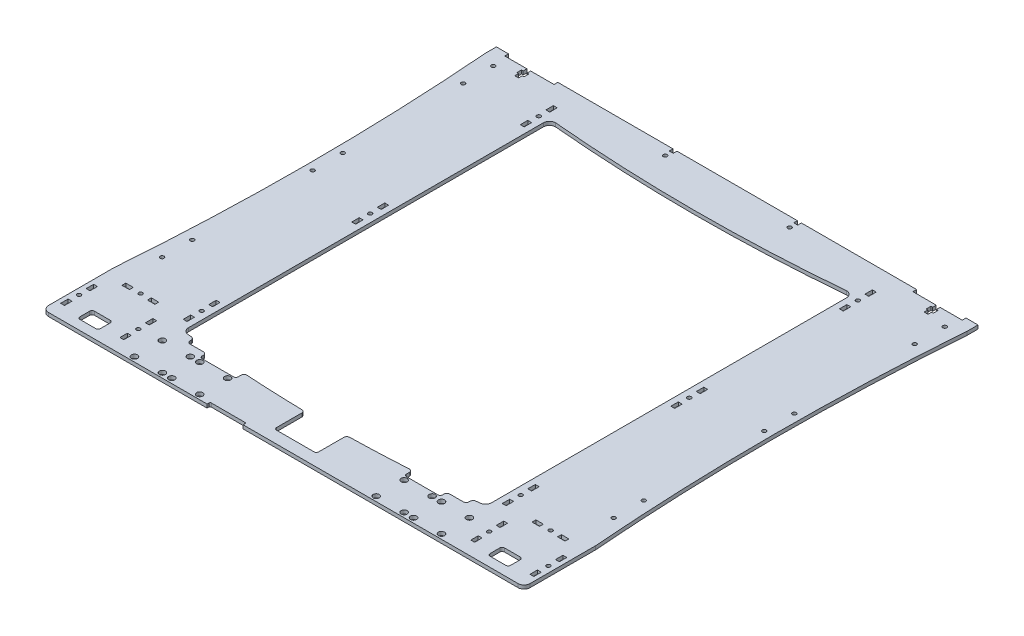
SolidWorks part; units mm, degrees
ref_plane "Alzado" through (0, 0, 0) normal (0, 0, 1) x (1, 0, 0)
ref_plane "Planta" through (0, 0, 0) normal (0, 1, 0) x (1, 0, 0)
ref_plane "Vista lateral" through (0, 0, 0) normal (1, 0, 0) x (0, 0, -1)
sketch "Croquis1" plane through (0, 0, 0) normal (0, 1, 0) x (1, 0, 0)
  line L0 (200, 377) -> (200, 0) construction
  line L1 (0, 0) -> (400, 0)
  line L2 (0, 0) -> (0, 377)
  line L3 (0, 377) -> (10, 377)
  line L4 (400, 0) -> (400, 377)
  line L5 (52.7, 17.8) -> (55.9, 17.8)
  line L6 (3.5, 17.8) -> (6.7, 17.8)
  line L7 (3.5, 17.8) -> (3.5, 11.6)
  line L8 (3.5, 11.6) -> (6.7, 11.6)
  line L9 (6.7, 17.8) -> (6.7, 11.6)
  line L10 (3.5, 39) -> (6.7, 39)
  line L11 (3.5, 39) -> (3.5, 32.8)
  line L12 (3.5, 32.8) -> (6.7, 32.8)
  line L13 (6.7, 39) -> (6.7, 32.8)
  line L14 (52.7, 17.8) -> (52.7, 11.6)
  line L15 (52.7, 11.6) -> (55.9, 11.6)
  line L16 (55.9, 17.8) -> (55.9, 11.6)
  line L17 (52.7, 39) -> (55.9, 39)
  line L18 (52.7, 39) -> (52.7, 32.8)
  line L19 (52.7, 32.8) -> (55.9, 32.8)
  line L20 (55.9, 39) -> (55.9, 32.8)
  line L21 (69.1, 218.4) -> (69.1, 212.2)
  line L22 (16, 53.2) -> (22.2, 53.2)
  line L23 (16, 53.2) -> (16, 50)
  line L24 (16, 50) -> (22.2, 50)
  line L25 (22.2, 53.2) -> (22.2, 50)
  line L26 (37.2, 53.2) -> (43.4, 53.2)
  line L27 (37.2, 53.2) -> (37.2, 50)
  line L28 (37.2, 50) -> (43.4, 50)
  line L29 (43.4, 53.2) -> (43.4, 50)
  line L30 (65.9, 57.2) -> (69.1, 57.2)
  line L31 (65.9, 57.2) -> (65.9, 51)
  line L32 (65.9, 51) -> (69.1, 51)
  line L33 (69.1, 57.2) -> (69.1, 51)
  line L34 (65.9, 78.4) -> (69.1, 78.4)
  line L35 (65.9, 78.4) -> (65.9, 72.2)
  line L36 (65.9, 72.2) -> (69.1, 72.2)
  line L37 (69.1, 78.4) -> (69.1, 72.2)
  line L38 (65.9, 218.4) -> (69.1, 218.4)
  line L39 (65.9, 218.4) -> (65.9, 212.2)
  line L40 (65.9, 212.2) -> (69.1, 212.2)
  line L41 (65.9, 197.2) -> (69.1, 197.2)
  line L42 (69.1, 197.2) -> (69.1, 191)
  line L43 (65.9, 197.2) -> (65.9, 191)
  line L44 (65.9, 191) -> (69.1, 191)
  line L45 (69.1, 78.4) -> (69.1, 218.4) construction
  line L46 (69.1, 337.2) -> (69.1, 331)
  line L47 (65.9, 337.2) -> (69.1, 337.2)
  line L48 (65.9, 337.2) -> (65.9, 331)
  line L49 (65.9, 331) -> (69.1, 331)
  line L50 (65.9, 352.2) -> (69.1, 352.2)
  line L51 (69.1, 358.4) -> (69.1, 352.2)
  line L52 (65.9, 358.4) -> (69.1, 358.4)
  line L53 (65.9, 358.4) -> (65.9, 352.2)
  line L54 (69.1, 197.2) -> (69.1, 337.2) construction
  line L55 (330.9, 197.2) -> (330.9, 337.2) construction
  line L56 (330.9, 78.4) -> (330.9, 218.4) construction
  line L57 (334.1, 358.4) -> (334.1, 352.2)
  line L58 (334.1, 358.4) -> (330.9, 358.4)
  line L59 (330.9, 358.4) -> (330.9, 352.2)
  line L60 (334.1, 352.2) -> (330.9, 352.2)
  line L61 (334.1, 331) -> (330.9, 331)
  line L62 (334.1, 337.2) -> (334.1, 331)
  line L63 (334.1, 337.2) -> (330.9, 337.2)
  line L64 (330.9, 337.2) -> (330.9, 331)
  line L65 (334.1, 191) -> (330.9, 191)
  line L66 (334.1, 197.2) -> (334.1, 191)
  line L67 (330.9, 197.2) -> (330.9, 191)
  line L68 (334.1, 197.2) -> (330.9, 197.2)
  line L69 (334.1, 212.2) -> (330.9, 212.2)
  line L70 (334.1, 218.4) -> (334.1, 212.2)
  line L71 (334.1, 218.4) -> (330.9, 218.4)
  line L72 (330.9, 78.4) -> (330.9, 72.2)
  line L73 (334.1, 72.2) -> (330.9, 72.2)
  line L74 (334.1, 78.4) -> (334.1, 72.2)
  line L75 (334.1, 78.4) -> (330.9, 78.4)
  line L76 (330.9, 57.2) -> (330.9, 51)
  line L77 (334.1, 51) -> (330.9, 51)
  line L78 (334.1, 57.2) -> (334.1, 51)
  line L79 (334.1, 57.2) -> (330.9, 57.2)
  line L80 (356.6, 53.2) -> (356.6, 50)
  line L81 (362.8, 50) -> (356.6, 50)
  line L82 (362.8, 53.2) -> (362.8, 50)
  line L83 (362.8, 53.2) -> (356.6, 53.2)
  line L84 (377.8, 53.2) -> (377.8, 50)
  line L85 (384, 50) -> (377.8, 50)
  line L86 (384, 53.2) -> (384, 50)
  line L87 (384, 53.2) -> (377.8, 53.2)
  line L88 (330.9, 218.4) -> (330.9, 212.2)
  line L89 (344.1, 39) -> (344.1, 32.8)
  line L90 (347.3, 32.8) -> (344.1, 32.8)
  line L91 (347.3, 39) -> (347.3, 32.8)
  line L92 (347.3, 39) -> (344.1, 39)
  line L93 (344.1, 17.8) -> (344.1, 11.6)
  line L94 (347.3, 11.6) -> (344.1, 11.6)
  line L95 (347.3, 17.8) -> (347.3, 11.6)
  line L96 (393.3, 39) -> (393.3, 32.8)
  line L97 (396.5, 32.8) -> (393.3, 32.8)
  line L98 (396.5, 39) -> (396.5, 32.8)
  line L99 (396.5, 39) -> (393.3, 39)
  line L100 (393.3, 17.8) -> (393.3, 11.6)
  line L101 (396.5, 11.6) -> (393.3, 11.6)
  line L102 (396.5, 17.8) -> (396.5, 11.6)
  line L103 (396.5, 17.8) -> (393.3, 17.8)
  line L104 (347.3, 17.8) -> (344.1, 17.8)
  line L105 (400, 0) -> (400, 377)
  line L106 (51, 377) -> (146.7, 377)
  line L108 (10, 377) -> (10, 373.9)
  line L109 (10, 373.9) -> (28.4, 373.9)
  line L110 (51, 377) -> (51, 373.9)
  line L111 (31.6, 373.9) -> (51, 373.9)
  line L113 (28.4, 373.9) -> (28.4, 370.9)
  line L114 (28.4, 363.9) -> (31.6, 363.9)
  line L115 (31.6, 373.9) -> (31.6, 370.9)
  line L116 (27, 370.9) -> (28.4, 370.9)
  line L117 (27, 370.9) -> (27, 366.9)
  line L118 (27, 366.9) -> (28.4, 366.9)
  line L119 (33, 370.9) -> (33, 366.9)
  line L120 (31.6, 370.9) -> (33, 370.9)
  line L121 (31.6, 366.9) -> (31.6, 363.9)
  line L122 (28.4, 366.9) -> (28.4, 363.9)
  line L123 (31.6, 366.9) -> (33, 366.9)
  line L124 (349, 377) -> (349, 373.9)
  line L125 (368.4, 373.9) -> (349, 373.9)
  line L126 (368.4, 373.9) -> (368.4, 370.9)
  line L127 (368.4, 370.9) -> (367, 370.9)
  line L128 (367, 370.9) -> (367, 366.9)
  line L129 (368.4, 366.9) -> (367, 366.9)
  line L130 (368.4, 366.9) -> (368.4, 363.9)
  line L131 (371.6, 363.9) -> (368.4, 363.9)
  line L132 (371.6, 366.9) -> (371.6, 363.9)
  line L133 (373, 366.9) -> (371.6, 366.9)
  line L134 (373, 370.9) -> (373, 366.9)
  line L135 (373, 370.9) -> (371.6, 370.9)
  line L136 (371.6, 373.9) -> (371.6, 370.9)
  line L137 (390, 373.9) -> (371.6, 373.9)
  line L138 (390, 377) -> (390, 373.9)
  line L139 (390, 377) -> (400, 377)
  line L140 (69.1, 51) -> (69.1, 0) construction
  line L141 (99.1, 31) -> (69.1, 0) construction
  line L142 (69.1, 0) -> (99.1, 0)
  line L143 (69.1, 0) -> (69.1, 31) construction
  line L144 (69.1, 31) -> (99.1, 31) construction
  line L145 (99.1, 0) -> (99.1, 31) construction
  line L146 (99.6, 0) -> (99.6, 37.4867) construction
  line L147 (72.5, 3.9) -> (95.7, 3.9) construction
  line L148 (72.5, 3.9) -> (72.5, 27.1) construction
  line L149 (72.5, 27.1) -> (95.7, 27.1) construction
  line L150 (95.7, 3.9) -> (95.7, 27.1) construction
  line L151 (72.5, 3.9) -> (95.7, 27.1) construction
  line L152 (72.5, 27.1) -> (95.7, 3.9) construction
  line L153 (150, 377) -> (250, 377)
  line L155 (146.7, 377) -> (146.7, 373.9)
  line L156 (146.7, 373.9) -> (150, 373.9)
  line L157 (150, 377) -> (150, 373.9)
  line L158 (148.35, 373.9) -> (148.35, 357.7293) construction
  line L159 (253.3, 377) -> (253.3, 373.9)
  line L160 (253.3, 373.9) -> (250, 373.9)
  line L161 (250, 377) -> (250, 373.9)
  line L162 (253.3, 377) -> (349, 377)
  line L163 (12.5, 366.9) -> (12.5, 0) construction
  circle A0 centre (5.1, 25.3) radius 1.6
  circle A1 centre (54.3, 25.3) radius 1.6
  circle A2 centre (67.5, 64.7) radius 1.6
  circle A3 centre (67.5, 204.7) radius 1.6
  circle A4 centre (67.5, 344.7) radius 1.6
  circle A5 centre (332.5, 344.7) radius 1.6
  circle A6 centre (332.5, 204.7) radius 1.6
  circle A7 centre (332.5, 64.7) radius 1.6
  circle A8 centre (345.7, 25.3) radius 1.6
  circle A9 centre (394.9, 25.3) radius 1.6
  circle A10 centre (29.7, 51.8) radius 1.6
  circle A11 centre (370.3, 51.8) radius 1.6
  circle A12 centre (72.5, 27.1) radius 2.55
  circle A13 centre (95.7, 27.1) radius 2.55
  circle A14 centre (72.5, 3.9) radius 2.55
  circle A15 centre (95.7, 3.9) radius 2.55
  circle A16 centre (327.5, 27.1) radius 2.55
  circle A17 centre (327.5, 3.9) radius 2.55
  circle A18 centre (304.3, 3.9) radius 2.55
  circle A19 centre (304.3, 27.1) radius 2.55
  circle A28 centre (103.5, 3.9) radius 2.55
  circle A29 centre (126.7, 3.9) radius 2.55
  circle A30 centre (126.7, 27.1) radius 2.55
  circle A31 centre (103.5, 27.1) radius 2.55
  circle A32 centre (273.3, 3.9) radius 2.55
  circle A33 centre (296.5, 3.9) radius 2.55
  circle A34 centre (296.5, 27.1) radius 2.55
  circle A35 centre (273.3, 27.1) radius 2.55
  circle A36 centre (148.35, 368.9) radius 1.6
  circle A37 centre (251.65, 368.9) radius 1.6
  circle A38 centre (12.5, 361.9) radius 1.6
  circle A39 centre (12.5, 336.9) radius 1.6
  circle A40 centre (12.5, 311.9) radius 1.6 [skipped]
  circle A41 centre (12.5, 286.9) radius 1.6 [skipped]
  circle A42 centre (12.5, 261.9) radius 1.6 [skipped]
  circle A43 centre (12.5, 236.9) radius 1.6
  circle A44 centre (12.5, 211.9) radius 1.6
  circle A45 centre (12.5, 186.9) radius 1.6 [skipped]
  circle A46 centre (12.5, 161.9) radius 1.6 [skipped]
  circle A48 centre (12.5, 111.9) radius 1.6
  circle A49 centre (12.5, 86.9) radius 1.6
  circle A50 centre (12.5, 136.9) radius 1.6 [skipped]
  circle A51 centre (387.5, 86.9) radius 1.6
  circle A52 centre (387.5, 111.9) radius 1.6
  circle A53 centre (387.5, 211.9) radius 1.6
  circle A54 centre (387.5, 236.9) radius 1.6
  circle A55 centre (387.5, 336.9) radius 1.6
  circle A56 centre (387.5, 361.9) radius 1.6
  point P43 (69.1, 54.1)
  point P168 (84.1, 15.5)
  point P219 (12.5, 73.9)
  dimension "D11" = 3.2
  dimension "D14" = 2
  dimension "D32" = 3.2
  dimension "D34" = 67.5
  dimension "D39" = 3.2
  dimension "D40" = 7.5
  dimension "D56" = 5.1
  dimension "D57" = 0.5
  dimension "D58" = 3.3
  dimension "D61" = 3.2
  dimension "D62" = 5
  dimension "D63" = 12.5
  dimension "D64" = 3.2
  dimension "D68" = 25
  dimension "D1" = 377
  dimension "D2" = 400
  dimension "D3" = 3.2
  dimension "D4" = 6.2
  dimension "D5" = 6.2
  dimension "D6" = 3.2
  dimension "D7" = 3.5
  dimension "D8" = 11.6
  dimension "D9" = 15
  dimension "D10" = 3.5
  dimension "D12" = 7.5
  dimension "D13" = 5.1
  dimension "D15" = 46
  dimension "D16" = 6.2
  dimension "D17" = 6.2
  dimension "D18" = 3.2
  dimension "D19" = 3.2
  dimension "D20" = 15
  dimension "D21" = 16
  dimension "D22" = 50
  dimension "D23" = 50
  dimension "D24" = 3.2
  dimension "D25" = 6.2
  dimension "D26" = 6.2
  dimension "D27" = 3.2
  dimension "D28" = 65.9
  dimension "D29" = 65.9
  dimension "D30" = 15
  dimension "D31" = 51
  dimension "D33" = 7.5
  dimension "D36" = 140
  dimension "D38" = 140
  dimension "D41" = 1.4
  dimension "D42" = 3.1
  dimension "D43" = 10
  dimension "D44" = 41
  dimension "D45" = 3.2
  dimension "D46" = 10
  dimension "D47" = 4
  dimension "D48" = 6
  dimension "D49" = 1.4
  dimension "D50" = 3
  dimension "D51" = 18.4
  dimension "D52" = 30
  dimension "D53" = 31
  dimension "D54" = 23.2
  dimension "D55" = 23.2
  dimension "D59" = 3.1
  dimension "D60" = 50
  dimension "D65" = 12
  dimension "D66" = 300
  dimension "D35" = 2
  dimension "D37" = 2
  dimension "D67" = 12
extrude "Saliente-Extruir1" add sketch "Croquis1" along normal blind 3 contours L1 L4 L3 L2 A8 A6 L57 L60 L59 L58 L34 L37 L36 L35 L30 L33 L32 L31 L26 L29 L28 L27 L22 L25 L24 L23 L17 L20 L19 L18 L5 L16 L15 L14 L10 L13 L12 L11 L6 L9
sketch "Croquis2" plane through (0, 3, 0) normal (0, 1, 0) x (1, 0, 0)
  line L0 (51, 377) -> (146.7, 377) construction
  line L1 (79.1, 347) -> (320.9, 347) construction
  line L2 (74.1, 342) -> (74.1, 47.1)
  line L3 (79.1, 42.1) -> (320.9, 42.1) construction
  line L4 (325.9, 342) -> (325.9, 47.1)
  line L5 (69.1, 337.2) -> (69.1, 331) construction
  line L6 (330.9, 337.2) -> (330.9, 331) construction
  circle A0 centre (273.3, 27.1) radius 2.55 construction
  arc A1 (325.9, 47.1) -> (320.9, 42.1) centre (320.9, 47.1) cw
  arc A2 (79.1, 347) -> (320.9, 347) centre (200, 1692.3457) ccw
  arc A3 (74.1, 342) -> (79.1, 347) centre (79.1, 342) cw
  arc A4 (320.9, 347) -> (325.9, 342) centre (320.9, 342) cw
  arc A5 (79.1, 42.1) -> (74.1, 47.1) centre (79.1, 47.1) cw
  arc A6 (79.1, 42.1) -> (320.9, 42.1) centre (200, 1082.7326) ccw
  dimension "D5" = 5
  dimension "D6" = 5
  dimension "D1" = 30
  dimension "D2" = 5
  dimension "D3" = 5
  dimension "D4" = 15
extrude "Cortar-Extruir1" cut sketch "Croquis2" against normal up to surface (3 mm away) up to face at (387.5, 0, -335.3)
fillet "Redondeo1" radius 5 2 edges at (400, 1.5, 0) (0, 1.5, 0)
sketch "Croquis4" plane through (0, 3, 0) normal (0, 1, 0) x (1, 0, 0)
  line L0 (0, 5) -> (0, 377) construction
  line L1 (0, 368) -> (6, 368) construction
  line L2 (0, 368) -> (0, 59.2)
  line L3 (0, 59.2) -> (6, 59.2) construction
  line L4 (6, 368) -> (6, 59.2) construction
  line L6 (10, 373.9) -> (28.4, 373.9) construction
  line L7 (200, 377) -> (200, 0) construction
  line L9 (150, 377) -> (250, 377) construction
  line L12 (5, 0) -> (395, 0) construction
  line L13 (400, 368) -> (400, 59.2)
  arc A0 (0, 368) -> (0, 59.2) centre (-1983.6133, 213.6) cw
  arc A2 (0, 368) -> (0, 59.2) centre (1983.6133, 213.6) ccw
  arc A3 (400, 368) -> (400, 59.2) centre (2383.6133, 213.6) ccw
  circle A4 centre (29.7, 51.8) radius 1.6 construction
  dimension "D2" = 7.4
  dimension "D1" = 5.9
  dimension "D3" = 6
extrude "Cortar-Extruir3" cut sketch "Croquis4" against normal up to surface (3 mm away) contours A0 L2 | L13 A3 up to face at (200, 0, -192.9974)
sketch "Croquis5" plane through (0, 3, 0) normal (0, 1, 0) x (1, 0, 0)
  line L0 (100.1, 29.335) -> (100.1, 41.5) construction
  line L5 (130.1, 28.5) -> (130.1, 47.9346) construction
  line L7 (200, 0) -> (200, 92.2455) construction
  line L8 (100.1, 30.5) -> (130.1, 30.5)
  line L9 (100.1, 30.5) -> (100.1, 41.5)
  line L10 (100.1, 41.5) -> (130.1, 41.5)
  line L11 (130.1, 30.5) -> (130.1, 41.5)
  line L12 (5, 0) -> (395, 0) construction
  line L13 (299.9, 30.5) -> (299.9, 41.5)
  line L14 (299.9, 30.5) -> (269.9, 30.5)
  line L15 (299.9, 41.5) -> (269.9, 41.5)
  line L16 (269.9, 30.5) -> (269.9, 41.5)
  line L17 (6.7, 17.8) -> (6.7, 11.6) construction
  line L18 (182.5, 35.2467) -> (217.5, 35.2467)
  line L19 (182.5, 35.2467) -> (182.5, 10)
  line L20 (182.5, 10) -> (217.5, 10)
  line L21 (217.5, 35.2467) -> (217.5, 10)
  line L22 (23.2, 20) -> (36.2, 20)
  line L23 (21.2, 18) -> (21.2, 10)
  line L24 (23.2, 8) -> (36.2, 8)
  line L25 (38.2, 18) -> (38.2, 10)
  line L27 (378.8, 18) -> (378.8, 10)
  line L28 (376.8, 8) -> (363.8, 8)
  line L29 (361.8, 18) -> (361.8, 10)
  line L30 (376.8, 20) -> (363.8, 20)
  arc A0 (79.1, 42.1) -> (320.9, 42.1) centre (200, 1082.7326) ccw construction
  arc A1 (23.2, 20) -> (21.2, 18) centre (23.2, 18) ccw
  arc A2 (38.2, 18) -> (36.2, 20) centre (36.2, 18) ccw
  arc A3 (36.2, 8) -> (38.2, 10) centre (36.2, 10) ccw
  arc A4 (23.2, 8) -> (21.2, 10) centre (23.2, 10) cw
  arc A5 (376.8, 20) -> (378.8, 18) centre (376.8, 18) cw
  arc A6 (376.8, 8) -> (378.8, 10) centre (376.8, 10) ccw
  arc A7 (363.8, 8) -> (361.8, 10) centre (363.8, 10) cw
  arc A8 (361.8, 18) -> (363.8, 20) centre (363.8, 18) cw
  circle A9 centre (103.5, 27.1) radius 2.55 construction
  point P36 (21.2, 20)
  point P37 (38.2, 20)
  point P40 (38.2, 8)
  dimension "D9" = 2
  dimension "D1" = 11
  dimension "D2" = 10
  dimension "D3" = 35
  dimension "D4" = 17.5
  dimension "D5" = 17
  dimension "D6" = 12
  dimension "D7" = 8
  dimension "D8" = 14.5
  dimension "D10" = 3.4
  dimension "D11" = 3.4
  dimension "D12" = 2.235
extrude "Cortar-Extruir4" cut sketch "Croquis5" against normal up to surface (3 mm away) up to face at (387.5, 0, -360.3)
fillet "Redondeo2" radius 2 6 edges at (299.9, 1.5, -30.5) (269.9, 1.5, -30.5) (100.1, 1.5, -30.5) (130.1, 1.5, -30.5) (217.5, 1.5, -10) (182.5, 1.5, -10)
sketch "Croquis6" plane through (0, 3, 0) normal (0, 1, 0) x (1, 0, 0)
  line L0 (5, 0) -> (395, 0) construction
  line L1 (136.7, 0) -> (166.7, 0)
  line L2 (136.7, 0) -> (136.7, 1.5)
  line L3 (137.7, 2.5) -> (165.7, 2.5)
  line L4 (166.7, 0) -> (166.7, 1.5)
  circle A0 centre (126.7, 3.9) radius 2.55 construction
  arc A1 (136.7, 1.5) -> (137.7, 2.5) centre (137.7, 1.5) cw
  arc A2 (165.7, 2.5) -> (166.7, 1.5) centre (165.7, 1.5) cw
  point P10 (136.7, 2.5)
  point P13 (166.7, 2.5)
  dimension "D4" = 1
  dimension "D1" = 30
  dimension "D2" = 2.5
  dimension "D3" = 10
extrude "Cortar-Extruir5" cut sketch "Croquis6" against normal up to surface (3 mm away)
sketch "Croquis7" plane through (0, 3, 0) normal (0, 1, 0) x (1, 0, 0)
  line L0 (200, 377) -> (200, 0) construction
  line L1 (150, 377) -> (250, 377) construction
  line L2 (166.7, 0) -> (395, 0) construction
  line L3 (100.1, 39.8745) -> (100.1, 32.5) construction
  line L4 (100.1, 36.0313) -> (84.1, 36.0313)
  line L5 (100.1, 36.0313) -> (100.1, 41.5313)
  line L6 (100.1, 41.5313) -> (84.1, 41.5313)
  line L7 (84.1, 36.0313) -> (84.1, 41.5313)
  line L8 (299.9, 41.5313) -> (315.9, 41.5313)
  line L9 (315.9, 36.0313) -> (315.9, 41.5313)
  line L10 (299.9, 36.0313) -> (299.9, 41.5313)
  line L11 (299.9, 36.0313) -> (315.9, 36.0313)
  arc A1 (79.1, 42.1) -> (100.1, 39.8745) centre (200, 1082.7326) ccw construction
  dimension "D1" = 5.5
  dimension "D3" = 16
extrude "Cortar-Extruir6" cut sketch "Croquis7" against normal up to surface (3 mm away)
fillet "Redondeo3" radius 2.5 10 edges at (269.9, 1.5, -37.435) (315.9, 1.5, -41.5313) (299.9, 1.5, -36.0313) (217.5, 1.5, -35.2467) (182.5, 1.5, -35.2467) (130.1, 1.5, -37.435) (100.1, 1.5, -36.0313) (84.1, 1.5, -41.5313) (315.9, 1.5, -36.0313) (84.1, 1.5, -36.0313)
